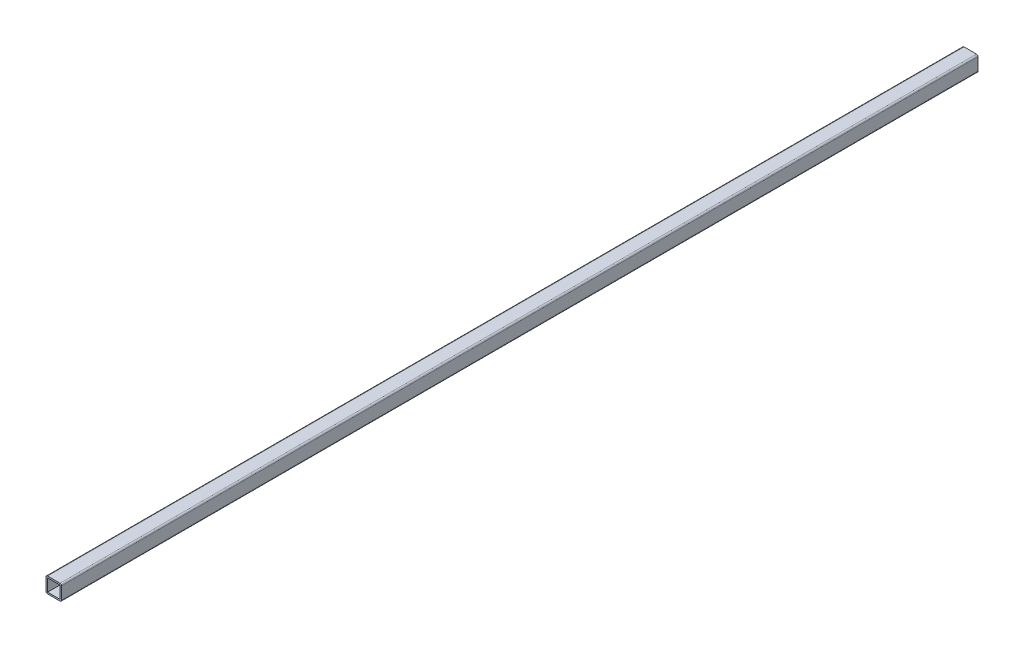
SolidWorks part; units mm, degrees
ref_plane "Front Plane" through (0, 0, 0) normal (0, 0, 1) x (1, 0, 0)
ref_plane "Top Plane" through (0, 0, 0) normal (0, 1, 0) x (1, 0, 0)
ref_plane "Right Plane" through (0, 0, 0) normal (1, 0, 0) x (0, 0, -1)
sketch "Sketch1" plane through (0, 0, 0) normal (0, 0, 1) x (1, 0, 0)
  line L0 (-10.16, 10.16) -> (-10.16, -10.16)
  line L1 (-10.16, 12.7) -> (10.16, 12.7)
  line L2 (-12.7, 10.16) -> (-12.7, -10.16)
  line L3 (-10.16, -12.7) -> (10.16, -12.7)
  line L4 (12.7, 10.16) -> (12.7, -10.16)
  line L5 (-12.7, 12.7) -> (12.7, -12.7) construction
  line L6 (-12.7, -12.7) -> (12.7, 12.7) construction
  line L7 (-10.16, -10.16) -> (10.16, -10.16)
  line L8 (10.16, 10.16) -> (10.16, -10.16)
  line L9 (-10.16, 10.16) -> (10.16, 10.16)
  line L10 (-12.7, 12.7) -> (-12.7, -12.7) construction
  line L11 (-12.7, -12.7) -> (12.7, -12.7) construction
  line L12 (12.7, 12.7) -> (12.7, -12.7) construction
  line L13 (-12.7, 12.7) -> (12.7, 12.7) construction
  arc A0 (-12.7, -10.16) -> (-10.16, -12.7) centre (-10.16, -10.16) ccw
  arc A1 (10.16, -12.7) -> (12.7, -10.16) centre (10.16, -10.16) ccw
  arc A2 (10.16, 12.7) -> (12.7, 10.16) centre (10.16, 10.16) cw
  arc A3 (-10.16, 12.7) -> (-12.7, 10.16) centre (-10.16, 10.16) ccw
  point P0 (0, 0)
  dimension "D4" = 2.54
  dimension "D1" = 25.4
  dimension "D2" = 25.4
  dimension "D3" = 2.54
extrude "Boss-Extrude1" add sketch "Sketch1" along normal blind 1500
